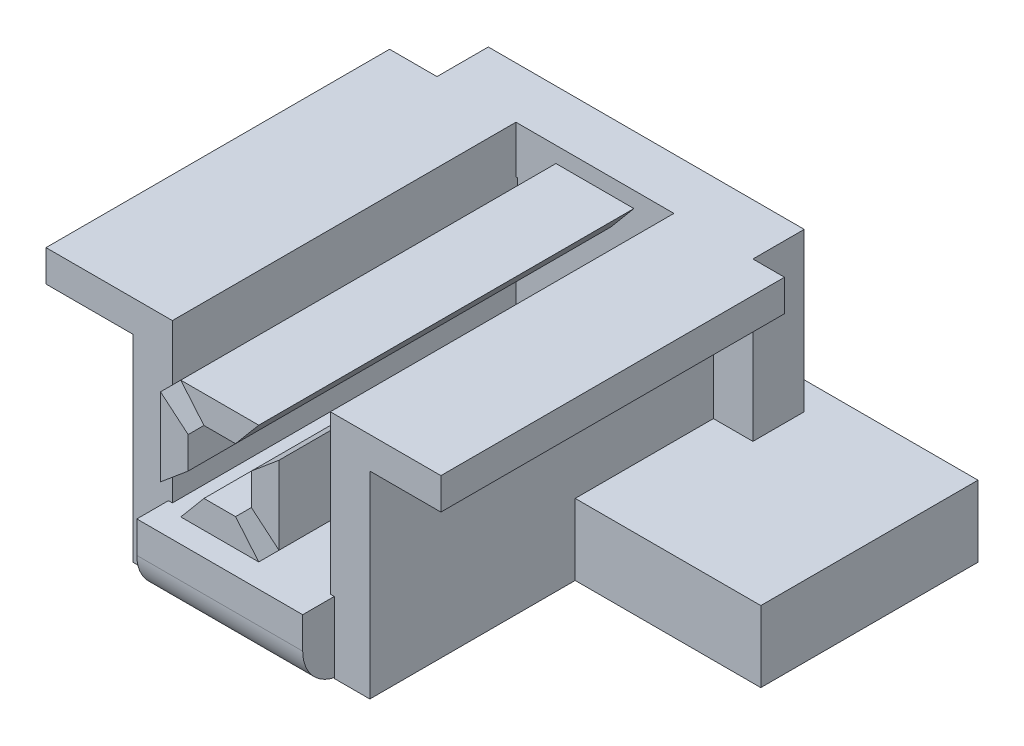
SolidWorks part; units mm, degrees
ref_plane "Front Plane" through (0, 0, 0) normal (0, 0, 1) x (1, 0, 0)
ref_plane "Top Plane" through (0, 0, 0) normal (0, 1, 0) x (1, 0, 0)
ref_plane "Right Plane" through (0, 0, 0) normal (1, 0, 0) x (0, 0, -1)
sketch "Sketch1" plane through (0, 0, 0) normal (0, 1, 0) x (1, 0, 0)
  line L0 (27.5, 55) -> (27.5, 0) construction
  line L1 (5, 0) -> (50, 0)
  line L2 (0, 5) -> (0, 50)
  line L3 (5, 55) -> (50, 55)
  line L4 (55, 5) -> (55, 50)
  line L5 (0, 55) -> (7.5, 55) construction
  line L6 (0, 55) -> (0, 47.5) construction
  line L7 (0, 47.5) -> (7.5, 47.5) construction
  line L8 (7.5, 55) -> (7.5, 47.5) construction
  line L9 (0, 27.5) -> (55, 27.5) construction
  circle A0 centre (7.5, 47.5) radius 2.5
  circle A1 centre (47.5, 47.5) radius 2.5
  circle A2 centre (47.5, 7.5) radius 2.5
  circle A3 centre (7.5, 7.5) radius 2.5
  arc A4 (50, 0) -> (55, 5) centre (50, 5) ccw
  arc A5 (50, 55) -> (55, 50) centre (50, 50) cw
  arc A6 (0, 50) -> (5, 55) centre (5, 50) cw
  arc A7 (5, 0) -> (0, 5) centre (5, 5) cw
  point P23 (55, 55)
  point P29 (0, 0)
  dimension "D3" = 2
  dimension "D5" = 5
  dimension "D1" = 55
  dimension "D2" = 55
  dimension "D4" = 2
extrude "Boss-Extrude2" add sketch "Sketch1" along normal blind 8 and the other way blind 1
sketch "Sketch2" plane through (0, 8, 0) normal (0, 1, 0) x (1, 0, 0)
  line L0 (0, 27.5) -> (55, 27.5)
  line L1 (0, 50) -> (0, 5) construction
  line L2 (55, 5) -> (55, 50) construction
  line L4 (0, 27.5) -> (55, 27.5)
  line L5 (0, 27.5) -> (0, 55)
  line L6 (0, 55) -> (55, 55)
  line L7 (55, 27.5) -> (55, 55)
  circle M3 centre (7.5, 47.5) radius 2.5
  line M5 (55, 5) -> (55, 50)
  arc M6 (55, 50) -> (50, 55) centre (50, 50) ccw
  line M7 (50, 55) -> (5, 55)
  arc M8 (5, 55) -> (0, 50) centre (5, 50) ccw
  line M9 (0, 50) -> (0, 5)
  circle M12 centre (47.5, 47.5) radius 2.5
  dimension "D1" = 27.5
extrude "Cut-Extrude1" cut sketch "Sketch2" against normal through all both and the other way through all contours L0 M9 M5 M6 M7 M8 M12 M3
sketch "Sketch3" plane through (0, 0, -27.5) normal (0, 0, -1) x (-1, 0, 0)
  line L0 (0, -1) -> (0, 8) construction
  line L1 (-55, -1) -> (-37.5, -1) construction
  line L2 (-55, -1) -> (-55, 3.5) construction
  line L3 (-55, 3.5) -> (-37.5, 3.5) construction
  line L4 (-37.5, -1) -> (-37.5, 3.5) construction
  line L5 (0, -1) -> (-55, -1) construction
  circle A0 centre (-37.5, 3.5) radius 3.25
  circle A1 centre (-17.5, 3.5) radius 3.25
  point P10 (0, 3.5)
  dimension "D3" = 6.5
  dimension "D4" = 2
  dimension "D5" = 17.5
  dimension "D1" = 4.5
  dimension "D2" = 17.5
  dimension "D6" = 4.5
sketch3d "3DSketch1"
  point P0 (9.6264, 4.1069, -27.5)
sketch "Sketch5" plane through (0, 8, 0) normal (0, 1, 0) x (1, 0, 0)
  line L0 (27.5, 27.5) -> (27.5, 0)
  line L1 (0, 27.5) -> (55, 27.5) construction
  line L2 (5, 0) -> (50, 0) construction
  line L3 (27.5, 27.5) -> (27.5, 24)
  line L5 (27.5, 24) -> (23, 24)
  line L6 (27.5, 24) -> (27.5, 17.5)
  line L7 (27.5, 17.5) -> (23, 17.5)
  line L8 (23, 24) -> (23, 17.5)
  line L9 (27.5, 24) -> (32, 24)
  line L10 (27.5, 24) -> (27.5, 17.5)
  line L11 (27.5, 17.5) -> (32, 17.5)
  line L12 (32, 24) -> (32, 17.5)
  dimension "D1" = 3.5
  dimension "D2" = 6.5
  dimension "D3" = 4.5
  dimension "D4" = 4.5
  dimension "D5" = 6.5
extrude "Cut-Extrude5" cut sketch "Sketch3" against normal blind 15 draft 0.057 contours A0 | A1
extrude "Boss-Extrude3" add sketch "Sketch5" along normal blind 14.5 contours L5 L8 L7 L0 | L12 L9 L0 L11
sketch "Sketch6" plane through (0, 0, -24) normal (0, 0, -1) x (-1, 0, 0)
  line L0 (-27.5, 8) -> (-27.5, 17)
  line L1 (-32, 8) -> (-23, 8) construction
  circle A0 centre (-27.5, 17) radius 4
  dimension "D2" = 8
  dimension "D1" = 9
extrude "Cut-Extrude4" cut sketch "Sketch6" against normal blind 1.5
sketch "Sketch11" plane through (0, 0, -24) normal (0, 0, -1) x (-1, 0, 0)
  line L0 (-27.5, 22.5) -> (-25.5, 22.5)
  line L1 (-32.4368, 26) -> (-22.5632, 26)
  line L2 (-32, 22.5) -> (-23, 22.5) construction
  line L3 (-25.5, 22.5) -> (-27.5, 22.5)
  line L4 (-25.5, 22.5) -> (-29.5, 22.5)
  line L5 (-25.5, 22.5) -> (-25.5, 26)
  line L6 (-25.5, 26) -> (-29.5, 26)
  line L7 (-29.5, 22.5) -> (-29.5, 26)
  line L8 (-22.5632, 26) -> (-25.5, 22.5)
  line L9 (-29.5, 22.5) -> (-32.4368, 26)
  point P10 (-27.5, 26)
  line M9 (-23, 22.5) -> (-32, 22.5)
  dimension "D1" = 2
  dimension "D2" = 4
  dimension "D3" = 3.5
  dimension "D4" = 40
sketch "Sketch12" plane through (0, 8, 0) normal (0, 1, 0) x (1, 0, 0)
  line L0 (27.5, 17.5) -> (27.5, 0)
  line L1 (32, 17.5) -> (23, 17.5) construction
  line L2 (5, 0) -> (50, 0) construction
  line L3 (17, 0) -> (17, -30)
  line L4 (17, 0) -> (38, 0)
  line L5 (27.5, 0) -> (27.5, -30)
  line L6 (17, -30) -> (38, -30)
  line L7 (38, 0) -> (38, -30)
  point P9 (23.9675, 0)
  line M9 (5, 0) -> (50, 0)
  dimension "D1" = 30
  dimension "D2" = 10.5
extrude "Boss-Extrude7" add sketch "Sketch12" against normal blind 9 contours L7 L5 L6 M9 | L3 L6 L5 M9
sketch "Sketch15" plane through (0, 22.5, 0) normal (0, 1, 0) x (1, 0, 0)
  line L0 (32, 24) -> (32, 17.5) construction
  line L1 (32, 17.5) -> (23, 17.5)
  line L2 (32, 17.5) -> (32, 24)
  line L3 (32, 24) -> (23, 24)
  line L4 (23, 17.5) -> (23, 24)
  line L5 (32, 17.5) -> (23, 17.5) construction
extrude "Boss-Extrude8" add sketch "Sketch15" along normal blind 3.5
extrude "Boss-Extrude9" add sketch "Sketch11" against normal blind 54 contours L9 L7 L1 | L7 L5 L1 M9 | L8 L1 L5
fillet "Fillet4" radius 5 1 edges at (27.5, -1, 30)
sketch "Sketch18" plane through (0, 26, 0) normal (0, 1, 0) x (1, 0, 0)
  line L0 (32.4368, -30) -> (32.4368, 24) construction
  line L1 (22.5632, 24) -> (32.4368, 24)
  line L2 (22.5632, 24) -> (22.5632, 17.5)
  line L3 (22.5632, 17.5) -> (32.4368, 17.5)
  line L4 (32.4368, 24) -> (32.4368, 17.5)
  dimension "D1" = 6.5
extrude "Boss-Extrude11" add sketch "Sketch18" along normal blind 0.5
sketch "Sketch20" plane through (0, 8, 0) normal (0, 1, 0) x (1, 0, 0)
  line L0 (27.5, -1030) -> (27.5, 48970) construction
  line L1 (17, -30) -> (38, -30) construction
  line L2 (32, 17.5) -> (23, 17.5) construction
  line L3 (27.5, 17.5) -> (16.5, 17.5)
  line L4 (27.5, 17.5) -> (27.5, 0)
  line L5 (27.5, 0) -> (16.5, 0)
  line L6 (16.5, 17.5) -> (16.5, 0)
  line L7 (27.5, 17.5) -> (16.5, 0) construction
  line L8 (27.5, 0) -> (16.5, 17.5) construction
  line L10 (27.5, 17.5) -> (38.5, 17.5)
  line L11 (27.5, 17.5) -> (27.5, 0)
  line L12 (27.5, 0) -> (38.5, 0)
  line L13 (38.5, 17.5) -> (38.5, 0)
  line L14 (27.5, 17.5) -> (38.5, 0) construction
  line L15 (27.5, 0) -> (38.5, 17.5) construction
  line L16 (38.5, 17.5) -> (42.5, 17.5)
  line L17 (38.5, 17.5) -> (38.5, 0)
  line L18 (38.5, 0) -> (42.5, 0)
  line L19 (42.5, 17.5) -> (42.5, 0)
  line L21 (16.5, 17.5) -> (12.5, 17.5)
  line L22 (16.5, 17.5) -> (16.5, 0)
  line L23 (16.5, 0) -> (12.5, 0)
  line L24 (12.5, 17.5) -> (12.5, 0)
  line L26 (42.5, 0) -> (38.5, 0)
  line L27 (42.5, 0) -> (42.5, 17.5)
  line L28 (42.5, 17.5) -> (38.5, 17.5)
  line L29 (38.5, 0) -> (38.5, 17.5)
  line L30 (16.5, 0) -> (12.5, 0)
  line L31 (16.5, 0) -> (16.5, 17.5)
  line L32 (16.5, 17.5) -> (12.5, 17.5)
  line L33 (12.5, 0) -> (12.5, 17.5)
  point P5 (27.5, -30)
  point P9 (22, 8.75)
  point P14 (33, 8.75)
  line M12 (5, 0) -> (17, 0)
  line M16 (38, 0) -> (50, 0)
  dimension "D2" = 11
  dimension "D3" = 17.5
  dimension "D4" = 4
extrude "Boss-Extrude12" add sketch "Sketch20" along normal blind 18 contours L21 L24 L6 M12 | L19 L16 L13 M16
sketch "Sketch21" plane through (12.5, 0, 0) normal (-1, 0, 0) x (0, 0, 1)
  line L0 (-17.5, 26) -> (-17.5, 8) construction
  line L1 (0, 26) -> (-17.5, 26)
  line L2 (0, 26) -> (0, 24)
  line L3 (0, 24) -> (-17.5, 24)
  line L4 (-17.5, 26) -> (-17.5, 24)
  dimension "D1" = 2
sketch "Sketch22" plane through (12.5, 0, 0) normal (-1, 0, 0) x (0, 0, 1)
  line L1 (-17.5, 24) -> (0, 24)
  line L2 (-17.5, 24) -> (-17.5, 28)
  line L3 (-17.5, 28) -> (0, 28)
  line L4 (0, 24) -> (0, 28)
  dimension "D1" = 4
extrude "Boss-Extrude13" add sketch "Sketch22" along normal blind 11 and the other way blind 4 contours L3 L4 L1 L2
sketch "Sketch25" plane through (0, 28, 0) normal (0, 1, 0) x (1, 0, 0)
  line L2 (1.5, 17.5) -> (16.5, 17.5) construction
  line L3 (1.5, 0) -> (3.5, 0)
  line L4 (1.5, 0) -> (1.5, 17.5)
  line L5 (1.5, 17.5) -> (3.5, 17.5)
  line L6 (3.5, 0) -> (3.5, 17.5)
  dimension "D1" = 2
extrude "Boss-Extrude14" add sketch "Sketch25" along normal blind 41
sketch "Sketch28" plane through (1.5, 0, 0) normal (-1, 0, 0) x (0, 0, 1)
  line L2 (0, 69) -> (-41, 69)
  line L3 (0, 69) -> (0, 24)
  line L4 (0, 24) -> (-41, 24)
  line L5 (-41, 69) -> (-41, 24)
  dimension "D1" = 45
  dimension "D2" = 41
extrude "Boss-Extrude15" add sketch "Sketch28" against normal blind 2
sketch "Sketch29" plane through (1.5, 0, 0) normal (-1, 0, 0) x (0, 0, 1)
  line L1 (0, 24) -> (-5, 24)
  line L2 (0, 24) -> (0, 33)
  line L3 (0, 33) -> (-5, 33)
  line L4 (-5, 24) -> (-5, 33)
  circle A0 centre (-5, 33) radius 1.75
  circle A1 centre (-36, 33) radius 1.75
  circle A2 centre (-36, 64) radius 1.75
  circle A3 centre (-5, 64) radius 1.75
  dimension "D3" = 3.5
  dimension "D6" = 31
  dimension "D1" = 9
  dimension "D2" = 5
  dimension "D7" = 31
  dimension "D4" = 2
  dimension "D5" = 2
extrude "Cut-Extrude8" cut sketch "Sketch29" against normal blind 9 contours A1 | A3 | A0 | A2
sketch "Sketch30" plane through (42.5, 0, 0) normal (1, 0, 0) x (0, 0, -1)
  line L0 (17.5, 26) -> (17.5, 8) construction
  line L1 (0, 26) -> (17.5, 26)
  line L2 (0, 26) -> (0, 24)
  line L3 (0, 24) -> (17.5, 24)
  line L4 (17.5, 26) -> (17.5, 24)
  line L6 (0, 24) -> (17.5, 24)
  line L7 (0, 24) -> (0, 28)
  line L8 (0, 28) -> (17.5, 28)
  line L9 (17.5, 24) -> (17.5, 28)
  line M4 (17.5, 8) -> (17.5, 26)
  line M5 (17.5, 26) -> (0, 26)
  line M6 (0, 26) -> (0, 8)
  dimension "D1" = 2
  dimension "D2" = 4
extrude "Boss-Extrude16" add sketch "Sketch30" along normal blind 9 and the other way blind 4 contours L3 M6 M4 M5 | L9 L8 L7 M5
sketch "Sketch31" plane through (3.5, 0, 0) normal (1, 0, 0) x (0, 0, -1)
  line L1 (41, 69) -> (20.5, 69)
  line L2 (41, 69) -> (41, 47)
  line L3 (41, 47) -> (20.5, 47)
  line L4 (20.5, 69) -> (20.5, 47)
  circle A0 centre (20.5, 47) radius 10
  dimension "D3" = 20
  dimension "D1" = 22
  dimension "D2" = 20.5
extrude "Cut-Extrude9" cut sketch "Sketch31" against normal blind 9 contours L4 A0 L3 | L3 A0 L4
sketch "Sketch32" plane through (0, 0, -17.5) normal (0, 0, -1) x (-1, 0, 0)
  line L1 (-16.5, 28) -> (-3.5, 28)
  line L2 (-16.5, 28) -> (-16.5, 24)
  line L3 (-16.5, 24) -> (-3.5, 24)
  line L4 (-3.5, 28) -> (-3.5, 24)
extrude "Boss-Extrude17" add sketch "Sketch32" along normal blind 23.5
sketch "Sketch33" plane through (0, 8, 0) normal (0, 1, 0) x (1, 0, 0)
  line L0 (38.5, 17.5) -> (38.5, 0)
  line L1 (38.5, 17.5) -> (38, 17.5)
  line L2 (38.5, 0) -> (38, 0)
  line L3 (38, 17.5) -> (38, 0)
  line L4 (16.5, 17.5) -> (16.5, 0)
  line L5 (16.5, 17.5) -> (17, 17.5)
  line L6 (16.5, 0) -> (17, 0)
  line L7 (17, 17.5) -> (17, 0)
  dimension "D1" = 0.5
  dimension "D2" = 0.5
extrude "Boss-Extrude18" add sketch "Sketch33" along normal blind 20
sketch "Sketch34" plane through (0, 0, 0) normal (0, 0, 1) x (1, 0, 0)
  line L0 (42.5, 24) -> (42.5, 8) construction
  line L1 (51.5, 28) -> (42.5, 28)
  line L2 (51.5, 28) -> (51.5, 24)
  line L3 (51.5, 24) -> (42.5, 24)
  line L4 (42.5, 28) -> (42.5, 24)
  line L5 (42.5, 24) -> (51.5, 24) construction
  line L7 (42.5, 28) -> (38, 28)
  line L8 (42.5, 28) -> (42.5, -1)
  line L9 (42.5, -1) -> (38, -1)
  line L10 (38, 28) -> (38, -1)
  line L11 (17, 28) -> (1.5, 28)
  line L12 (17, 28) -> (17, 24)
  line L13 (17, 24) -> (1.5, 24)
  line L14 (1.5, 28) -> (1.5, 24)
  line L15 (12.5, 24) -> (17, 24)
  line L16 (12.5, 24) -> (12.5, -1)
  line L17 (12.5, -1) -> (17, -1)
  line L18 (17, 24) -> (17, -1)
  line M1 (42.5, 8) -> (42.5, 24)
  line M2 (42.5, 24) -> (51.5, 24)
  line M3 (51.5, 24) -> (51.5, 28)
  line M4 (51.5, 28) -> (38, 28)
  line M5 (38, 28) -> (38, 8)
  line M6 (38, 8) -> (38, -1)
  line M7 (38, -1) -> (50, -1)
extrude "Boss-Extrude19" add sketch "Sketch34" along normal blind 26 contours L18 L13 L16 L17 | L11 L14 L13 L12 | L8 L4 M1 M4 M5 M6 M7 | L4 M4 M2 M3
sketch "Sketch35" plane through (0, 0, -17.5) normal (0, 0, 1) x (1, 0, 0)
  line L1 (32.4368, 26.5) -> (22.5632, 26.5)
  line L2 (32.4368, 26.5) -> (32.4368, 26)
  line L3 (32.4368, 26) -> (22.5632, 26)
  line L4 (22.5632, 26.5) -> (22.5632, 26)
extrude "Boss-Extrude20" add sketch "Sketch35" along normal blind 47.5
sketch "Sketch37" plane through (0, 0, -17.5) normal (0, 0, 1) x (1, 0, 0)
  line L0 (27.5, 8) -> (29.5, 8)
  line L2 (32, 8) -> (23, 8) construction
  line L3 (29.5, 12) -> (33.1362, 7.6666)
  line L4 (29.5, 8) -> (25.5, 8)
  line L5 (29.5, 8) -> (29.5, 12)
  line L6 (29.5, 12) -> (25.5, 12)
  line L7 (25.5, 8) -> (25.5, 12)
  line L8 (25.5, 12) -> (21.8638, 7.6666)
  line L9 (21.8638, 7.6666) -> (33.1362, 7.6666)
  line M8 (32, 8) -> (32, 25.4794)
  line M12 (23, 25.4794) -> (23, 8)
  line M13 (23, 8) -> (32, 8)
  dimension "D1" = 2
  dimension "D2" = 4
  dimension "D3" = 4
  dimension "D4" = 40
  dimension "D5" = 40
extrude "Boss-Extrude21" add sketch "Sketch37" along normal blind 47.5 contours L7 L8 M12 M13 | L7 L5 L6 M13 | L5 L3 M13 M8 | L8 L9 L3 M8 M13 M12
sketch "Sketch38" plane through (0, 0, 30) normal (0, 0, 1) x (1, 0, 0)
  line L1 (22.5632, 26.5) -> (22.1436, 26.5)
  line L2 (22.5632, 26.5) -> (22.5632, 8)
  line L3 (22.5632, 8) -> (22.1436, 8)
  line L4 (22.1436, 26.5) -> (22.1436, 8)
  line L5 (32.4368, 26.5) -> (32.8564, 26.5)
  line L6 (32.4368, 26.5) -> (32.4368, 8)
  line L7 (32.4368, 8) -> (32.8564, 8)
  line L8 (32.8564, 26.5) -> (32.8564, 8)
extrude "Cut-Extrude10" cut sketch "Sketch38" against normal blind 90.5
sketch "Sketch39" plane through (0, 0, 30) normal (0, 0, 1) x (1, 0, 0)
  line L0 (27.784, 26.1035) -> (27.5, 26.5)
  line L1 (32.4368, 26.5) -> (38, 26.5)
  line L2 (32.4368, 26.5) -> (32.4368, 8)
  line L3 (32.4368, 8) -> (38, 8)
  line L4 (38, 26.5) -> (38, 8)
  line L5 (32.4368, 26.5) -> (22.5632, 26.5) construction
  line L6 (27.5, 26.5) -> (27.5, 8)
  line L7 (38, 17.25) -> (38, 19.25)
  line L8 (34, 19.25) -> (38, 22.6064)
  line L9 (38, 19.25) -> (34, 19.25)
  line L10 (38, 19.25) -> (38, 15.25)
  line L11 (38, 15.25) -> (34, 15.25)
  line L12 (34, 19.25) -> (34, 15.25)
  line L13 (34, 15.25) -> (38, 11.8936)
  line L14 (22.5632, 8.5) -> (21.9673, 8)
  line L15 (17, 8) -> (22.5632, 8) construction
  line L16 (17, 22.6064) -> (17.7151, 22.6064)
  line L17 (38, 22.6064) -> (37.2849, 22.6064)
  line L18 (38, 22.6064) -> (38, 22.0064)
  line L19 (38, 22.0064) -> (37.2849, 22.0064)
  line L20 (37.2849, 22.6064) -> (37.2849, 22.0064)
  line L21 (38, 11.8936) -> (37.2849, 11.8936)
  line L22 (38, 11.8936) -> (38, 12.4936)
  line L23 (38, 12.4936) -> (37.2849, 12.4936)
  line L24 (37.2849, 11.8936) -> (37.2849, 12.4936)
  line L25 (17.7151, 22.6064) -> (17.7151, 22.0064)
  line L26 (17, 22.0064) -> (17.7151, 22.0064)
  line L27 (21, 19.25) -> (17, 22.6064)
  line L28 (21, 19.25) -> (21, 15.25)
  line L29 (17, 19.25) -> (21, 19.25)
  line L30 (17.7151, 11.8936) -> (17.7151, 12.4936)
  line L31 (17, 11.8936) -> (17.7151, 11.8936)
  line L32 (17, 12.4936) -> (17.7151, 12.4936)
  line L33 (17, 26.5) -> (17, 8)
  line L34 (17, 15.25) -> (21, 15.25)
  line L35 (21, 15.25) -> (17, 11.8936)
  line L36 (17, 19.25) -> (17, 22.0064)
  line L37 (17, 22.0064) -> (17.7151, 22.0064)
  line L38 (17.7151, 22.0064) -> (21, 19.25)
  line L39 (17, 19.25) -> (21, 19.25)
  dimension "D1" = 2
  dimension "D2" = 4
  dimension "D3" = 4
  dimension "D4" = 40
  dimension "D5" = 40
  dimension "D6" = 0.6
  dimension "D7" = 0.6
extrude "Boss-Extrude23" add sketch "Sketch39" against normal blind 47.5 contours L26 L33 L29 L27 | L33 L34 L28 L29 | L35 L34 L33 L32 | L23 L4 L11 L13 | L9 L12 L11 L4 | L4 L19 L8 L9
ref_plane "Plane1" through (5, 8, 0) normal (0, 1, 0) x (1, 0, 0)
sketch "Sketch45" plane through (0, 8, 0) normal (0, 1, 0) x (1, 0, 0)
  line L0 (0, 15.4413) -> (0, -89.262) construction
  line L1 (-11, 15.4413) -> (-11, -89.262)
  dimension "D1" = 11
sketch "Sketch46" plane through (0, 0, 0) normal (-1, 0, 0) x (0, 0, 1)
  line L1 (-27.5, -1) -> (-5, -1)
  line L2 (-27.5, -1) -> (-27.5, 8)
  line L3 (-27.5, 8) -> (-5, 8)
  line L4 (-5, -1) -> (-5, 8)
  line L5 (-27.5, 8) -> (0, 8)
  line L6 (-27.5, 8) -> (-27.5, -1)
  line L7 (-27.5, -1) -> (0, -1)
  line L8 (0, 8) -> (0, -1)
  line M2 (-27.5, 8) -> (-27.5, -1)
  line M3 (-27.5, -1) -> (-5, -1)
  line M4 (-5, -1) -> (-5, 8)
  line M5 (-5, 8) -> (-27.5, 8)
  dimension "D1" = 27.5
extrude "Boss-Extrude26" add sketch "Sketch46" against normal blind 11.5 contours M5 M2 M3 M4 | L8 L5 L7 M4
sketch "Sketch47" plane through (0, 0, 0) normal (-1, 0, 0) x (0, 0, 1)
  line L1 (-27.5, 8) -> (0, 8)
  line L2 (-27.5, 8) -> (-27.5, -1)
  line L3 (-27.5, -1) -> (0, -1)
  line L4 (0, 8) -> (0, -1)
extrude "Boss-Extrude27" add sketch "Sketch47" along normal blind 11
sketch "Sketch48" plane through (0, 8, 0) normal (0, 1, 0) x (1, 0, 0)
  line L0 (12.5, 17.5) -> (12.5, 24)
  line L1 (23, 24) -> (12.5, 24)
  line L2 (23, 24) -> (23, 17.5)
  line L3 (23, 17.5) -> (12.5, 17.5)
  line L4 (12.5, 24) -> (12.5, 17.5)
  line L5 (12.5, 17.5) -> (7.5, 17.5)
  line L6 (12.5, 24) -> (7.5, 24)
  line L7 (7.5, 17.5) -> (7.5, 24)
  line L8 (42.5, 24) -> (42.5, 17.5)
  line L9 (32, 24) -> (42.5, 24)
  line L10 (32, 24) -> (32, 17.5)
  line L11 (32, 17.5) -> (42.5, 17.5)
  line L12 (42.5, 24) -> (42.5, 17.5)
  line L13 (42.5, 24) -> (47.5, 24)
  line L14 (42.5, 17.5) -> (47.5, 17.5)
  line L15 (47.5, 24) -> (47.5, 17.5)
  line M3 (12.5, 17.5) -> (17, 17.5)
  line M8 (22.5632, 17.5) -> (23, 17.5)
  line M9 (23, 17.5) -> (23, 24)
  line M11 (32, 24) -> (32, 17.5)
  line M12 (32, 17.5) -> (32.4368, 17.5)
  line M17 (38, 17.5) -> (42.5, 17.5)
  dimension "D1" = 5
  dimension "D2" = 5
sketch "Sketch49" plane through (0, 0, -24) normal (0, 0, -1) x (-1, 0, 0)
  line L0 (-17.5, 3.5) -> (-27.5, 17)
  line L1 (-27.5, 17) -> (-17.5, 17)
  line L2 (-17.5, 17) -> (-17.5, 3.5)
  line L3 (-27.5, 17) -> (-37.5, 3.5)
  line L4 (-37.5, 3.5) -> (-37.5, 17)
  line L5 (-37.5, 17) -> (-27.5, 17)
  circle A0 centre (-37.5, 17) radius 4
  circle A1 centre (-17.5, 17) radius 4
  dimension "D1" = 8
  dimension "D2" = 8
extrude "Boss-Extrude31" add sketch "Sketch48" along normal blind 18.5 contours L11 L8 L9 M12 M17 M11 | L15 L13 L8 L14 | L3 L1 L0 M8 M9 M3 | L7 L5 L0 L6
sketch "Sketch50" plane through (0, 0, -24) normal (0, 0, -1) x (-1, 0, 0)
  circle A0 centre (-17.5, 17) radius 4
  circle A1 centre (-37.5, 17) radius 4
  dimension "D1" = 8
  dimension "D2" = 8
extrude "Cut-Extrude11" cut sketch "Sketch50" against normal blind 1.5
sketch "Sketch51" plane through (0, 0, -24) normal (0, 0, -1) x (-1, 0, 0)
  line L1 (-32.4593, 12.5515) -> (-22.8331, 12.5515)
  line L2 (-32.4593, 12.5515) -> (-32.4593, 21.6767)
  line L3 (-32.4593, 21.6767) -> (-22.8331, 21.6767)
  line L4 (-22.8331, 12.5515) -> (-22.8331, 21.6767)
extrude "Boss-Extrude32" add sketch "Sketch51" against normal blind 1.5
sketch "Sketch53" plane through (0, 0, -24) normal (0, 0, -1) x (-1, 0, 0)
  line L0 (-27.5, 17) -> (-27.5, 8)
  line L1 (-47.5, 8) -> (-7.5, 8) construction
  line L2 (-27.5, 8) -> (-27.5, 26.5)
  line L3 (-47.5, 26.5) -> (-16.5, 26.5) construction
  line L4 (-27.5, 17.25) -> (-23.5, 17.25)
  line L5 (-23.5, 17.25) -> (-31.5, 17.25)
  line L7 (-31.5, 13.25) -> (-23.5, 13.25)
  line L8 (-31.5, 13.25) -> (-31.5, 21.25)
  line L9 (-31.5, 21.25) -> (-23.5, 21.25)
  line L10 (-23.5, 13.25) -> (-23.5, 21.25)
  line L11 (-31.5, 13.25) -> (-23.5, 21.25) construction
  line L12 (-31.5, 21.25) -> (-23.5, 13.25) construction
  dimension "D1" = 4
  dimension "D2" = 4
  dimension "D3" = 8
  dimension "D4" = 8
sketch "Sketch54" plane through (0, 0, -17.5) normal (0, 0, 1) x (1, 0, 0)
  line L0 (27.5, 22.5) -> (27.5, 14.5)
  line L1 (29.5, 22.5) -> (25.5, 22.5) construction
  line L3 (23.5, 22.5) -> (31.5, 22.5)
  line L4 (23.5, 22.5) -> (23.5, 14.5)
  line L5 (23.5, 14.5) -> (31.5, 14.5)
  line L6 (31.5, 22.5) -> (31.5, 14.5)
  line L7 (23.5, 22.5) -> (31.5, 14.5) construction
  line L8 (23.5, 14.5) -> (31.5, 22.5) construction
  point P4 (27.5, 18.5)
  line M17 (29.5, 22.5) -> (25.5, 22.5)
  dimension "D1" = 8
  dimension "D2" = 8
  dimension "D3" = 8
extrude "Boss-Extrude35" add sketch "Sketch54" along normal blind 47.5 contours L6 L3 L0 L5 M17 | L4 L5 L0 L3 M17
sketch "Sketch55" plane through (0, 0, 30) normal (0, 0, 1) x (1, 0, 0)
  line L1 (32.4368, 26.5) -> (22.5632, 26.5)
  line L2 (32.4368, 26.5) -> (32.4368, 26)
  line L3 (32.4368, 26) -> (22.5632, 26)
  line L4 (22.5632, 26.5) -> (22.5632, 26)
extrude "Cut-Extrude12" cut sketch "Sketch55" against normal blind 47.5
sketch "Sketch56" plane through (0, 0, 26) normal (0, 0, 1) x (1, 0, 0)
  line L1 (38, 28) -> (37.5, 28)
  line L2 (38, 28) -> (38, 8)
  line L3 (38, 8) -> (37.5, 8)
  line L4 (37.5, 28) -> (37.5, 8)
  line L5 (17, 28) -> (17.5, 28)
  line L6 (17, 28) -> (17, 8)
  line L7 (17, 8) -> (17.5, 8)
  line L8 (17.5, 28) -> (17.5, 8)
  dimension "D1" = 0.5
  dimension "D2" = 0.5
extrude "Boss-Extrude36" add sketch "Sketch56" against normal blind 43.5
sketch "Sketch57" plane through (0, 0, 30) normal (0, 0, 1) x (1, 0, 0)
  line L0 (31.5, 20.5) -> (31.5, 16.5)
  line L1 (35, 18.4644) -> (35, 13.5632)
  line L2 (25.5, 22.5) -> (29.5, 22.5)
  line L3 (29.5, 22.5) -> (32.4368, 26)
  line L4 (29.5, 22.5) -> (29.5, 26)
  line L5 (22.5632, 26) -> (32.4368, 26) construction
  line L6 (31.5, 22.5) -> (31.5, 14.5) construction
  line L7 (35, 13.5632) -> (31.5, 16.5)
  line L8 (31.5, 16.5) -> (35, 16.5)
  line L9 (31.5, 16.5) -> (31.5, 20.4288)
  line L10 (31.5, 20.4288) -> (35, 20.4288)
  line L11 (35, 16.5) -> (35, 20.4288)
  line L12 (35, 18.5356) -> (35, 23.4368)
  line L13 (35, 16.5) -> (31.5, 16.5)
  line L14 (35, 16.5) -> (35, 18.5)
  line L15 (35, 18.5) -> (31.5, 18.5)
  line L16 (31.5, 16.5) -> (31.5, 18.5)
  line L17 (35, 23.4368) -> (31.5, 20.5)
  line L18 (27.5, 22.5) -> (27.5, 14.5) construction
  line L19 (23.5, 14.5) -> (31.5, 14.5) construction
  line L20 (20, 13.5632) -> (23.5, 16.5)
  line L21 (23.5, 16.5) -> (20, 16.5)
  line L22 (20, 18.4644) -> (20, 13.5632)
  line L23 (20, 18.5356) -> (20, 23.4368)
  line L24 (20, 23.4368) -> (23.5, 20.5)
  line L25 (23.5, 20.5) -> (23.5, 16.5)
  line L26 (27.5, 18.5) -> (31.5, 18.5) construction
  line L27 (31.5, 18.5) -> (23.5, 18.5) construction
  line L28 (23.5, 20.5) -> (23.5, 16.5)
  line L29 (32.4368, 26) -> (22.5632, 26)
  line L30 (22.5632, 26) -> (25.5, 22.5)
  line L31 (25.5, 14.5) -> (29.5, 14.5)
  line L32 (22.5632, 11) -> (25.5, 14.5)
  line L33 (32.4368, 11) -> (22.5632, 11)
  line L34 (29.5, 14.5) -> (32.4368, 11)
  line L35 (23.5, 16.5) -> (20, 13.5632)
  line L36 (20, 13.5632) -> (20, 23.4368)
  line L37 (20, 23.4368) -> (23.5, 20.5)
  line L38 (23.5, 18.5) -> (23.5, 20.5)
  line M12 (23.5, 22.5) -> (23.5, 14.5)
  line M13 (23.5, 14.5) -> (31.5, 14.5)
  line M14 (31.5, 14.5) -> (31.5, 22.5)
  dimension "D1" = 2
  dimension "D2" = 3.5
  dimension "D3" = 130
extrude "Boss-Extrude37" add sketch "Sketch57" against normal blind 47.5 contours L12 L17 L0 L10 | L15 L11 L10 L9 | L11 L15 L8 L1 M14 | L8 L7 L1 | L34 L32 L33 M13 | L36 L22 L21 L28 L24 L23 M12 | L21 L22 L20
sketch "Sketch58" plane through (0, 0, 30) normal (0, 0, 1) x (1, 0, 0)
  line L1 (38, 22.0064) -> (37.2849, 22.0064)
  line L2 (38, 22.0064) -> (38, 12.4936)
  line L3 (38, 12.4936) -> (37.2849, 12.4936)
  line L4 (37.2849, 22.0064) -> (37.2849, 12.4936)
  line L5 (17, 22.0064) -> (17.7151, 22.0064)
  line L6 (17, 22.0064) -> (17, 12.4936)
  line L7 (17, 12.4936) -> (17.7151, 12.4936)
  line L8 (17.7151, 22.0064) -> (17.7151, 12.4936)
extrude "Cut-Extrude13" cut sketch "Sketch58" against normal blind 4
sketch "Sketch59" plane through (0, 0, 30) normal (0, 0, 1) x (1, 0, 0)
  line L0 (37.2849, 22.0064) -> (35, 20.0891)
  line L1 (35, 20.0891) -> (35, 14.4109)
  line L2 (35, 14.4109) -> (37.2849, 12.4936)
  line L3 (37.2849, 12.4936) -> (37.2849, 22.0064)
  line L4 (17.7151, 22.0064) -> (20, 20.0891)
  line L5 (20, 20.0891) -> (20, 14.4109)
  line L6 (20, 14.4109) -> (17.7151, 12.4936)
  line L7 (20, 14.4109) -> (17.7151, 12.4936) construction
  line L8 (17.7151, 12.4936) -> (17.7151, 22.0064)
extrude "Cut-Extrude15" cut sketch "Sketch59" against normal blind 47.5
sketch "Sketch60" plane through (0, 0, 26) normal (0, 0, 1) x (1, 0, 0)
  line L0 (17.7151, 12.4936) -> (17.7151, 22.0064) construction
  line L1 (37.2849, 22.0064) -> (37.5, 22.0064)
  line L2 (37.2849, 22.0064) -> (37.2849, 12.4936)
  line L3 (37.2849, 12.4936) -> (37.5, 12.4936)
  line L4 (37.5, 22.0064) -> (37.5, 12.4936)
  line L5 (17.5, 22.0064) -> (17.7151, 22.0064)
  line L6 (17.5, 22.0064) -> (17.5, 12.4936)
  line L7 (17.5, 12.4936) -> (17.7151, 12.4936)
  line L8 (17.7151, 22.0064) -> (17.7151, 12.4936)
extrude "Cut-Extrude16" cut sketch "Sketch60" against normal blind 47.5
sketch "Sketch61" plane through (0, 0, 30) normal (0, 0, 1) x (1, 0, 0)
  line L0 (32.4368, 8) -> (22.5632, 8)
  line L1 (22.5632, 8) -> (22.5632, 8.5)
  line L2 (22.5632, 8.5) -> (24.6609, 11)
  line L3 (24.6609, 11) -> (30.3391, 11)
  line L4 (30.3391, 11) -> (32.4368, 8.5)
  line L5 (32.4368, 8.5) -> (32.4368, 8)
extrude "Cut-Extrude17" cut sketch "Sketch61" against normal blind 47.5
sketch "Sketch62" plane through (0, 0, 30) normal (0, 0, 1) x (1, 0, 0)
  line L1 (23.5, 22.5) -> (31.5, 22.5)
  line L2 (23.5, 22.5) -> (23.5, 14.5)
  line L3 (23.5, 14.5) -> (31.5, 14.5)
  line L4 (31.5, 22.5) -> (31.5, 14.5)
extrude "Cut-Extrude18" cut sketch "Sketch62" against normal blind 47.5
sketch "Sketch63" plane through (0, 0, -41) normal (0, 0, -1) x (-1, 0, 0)
  line L1 (-3.5, 28) -> (-16.5, 28)
  line L2 (-3.5, 28) -> (-3.5, 24)
  line L3 (-3.5, 24) -> (-16.5, 24)
  line L4 (-16.5, 28) -> (-16.5, 24)
extrude "Cut-Extrude20" cut sketch "Sketch63" against normal blind 17
sketch "Sketch64" plane through (0, 0, -17.5) normal (0, 0, -1) x (-1, 0, 0)
  line L1 (-17.5, 26.5) -> (-16.5, 26.5)
  line L2 (-17.5, 26.5) -> (-17.5, 28)
  line L3 (-17.5, 28) -> (-16.5, 28)
  line L4 (-16.5, 26.5) -> (-16.5, 28)
extrude "Boss-Extrude38" add sketch "Sketch64" along normal blind 6.5
sketch "Sketch65" plane through (0, 8, 0) normal (0, 1, 0) x (1, 0, 0)
  line L0 (-11, 0) -> (0, 0)
  line L2 (-11, 27.5) -> (0, 27.5)
  line L3 (-11, 27.5) -> (-11, 0)
  line L4 (0, 0) -> (7.5, 0)
  line L5 (0, 0) -> (0, 7.5)
  line L6 (0, 7.5) -> (7.5, 7.5)
  line L7 (7.5, 0) -> (7.5, 7.5)
  line L8 (-11, 0) -> (0, 0)
  line L9 (0, 27.5) -> (0, 0)
  circle A0 centre (47.5, 7.5) radius 2.5
  circle A1 centre (7.5, 7.5) radius 2.5
  line M13 (55, 27.5) -> (-11, 27.5)
  line M14 (-11, 27.5) -> (-11, 0)
  line M15 (-11, 0) -> (12.5, 0)
  dimension "D1" = 7.5
  dimension "D3" = 5
  dimension "D2" = 7.5
extrude "Cut-Extrude22" cut sketch "Sketch65" against normal blind 9 contours L9 L5 M13 M14 M15 | L7 A1 L6 | L6 A1 L7
fillet "Fillet6" radius 5 1 edges at (0, 3.5, 0)
sketch "Sketch67" plane through (55, 0, 0) normal (1, 0, 0) x (0, 0, -1)
  line L1 (27.5, 8) -> (0, 8)
  line L2 (27.5, 8) -> (27.5, -1)
  line L3 (27.5, -1) -> (0, -1)
  line L4 (0, 8) -> (0, -1)
extrude "Boss-Extrude39" add sketch "Sketch67" along normal blind 11 and the other way blind 10
sketch "Sketch68" plane through (0, 0, -41) normal (0, 0, -1) x (-1, 0, 0)
  line L1 (-1.5, 69) -> (-3.5, 69)
  line L2 (-1.5, 69) -> (-1.5, 24)
  line L3 (-1.5, 24) -> (-3.5, 24)
  line L4 (-3.5, 69) -> (-3.5, 24)
extrude "Cut-Extrude23" cut sketch "Sketch68" against normal blind 17
sketch "Sketch69" plane through (0, 0, -24) normal (0, 0, -1) x (-1, 0, 0)
  line L1 (-3.5, 28) -> (-1.5, 28)
  line L2 (-3.5, 28) -> (-3.5, 69)
  line L3 (-3.5, 69) -> (-1.5, 69)
  line L4 (-1.5, 28) -> (-1.5, 69)
extrude "Cut-Extrude24" cut sketch "Sketch69" against normal blind 37
sketch "Sketch70" plane through (0, 0, -24) normal (0, 0, -1) x (-1, 0, 0)
  line L1 (-17.5, 26.5) -> (-1.5, 26.5)
  line L2 (-17.5, 26.5) -> (-17.5, 28)
  line L3 (-17.5, 28) -> (-1.5, 28)
  line L4 (-1.5, 26.5) -> (-1.5, 28)
  line L5 (-7.5, 24) -> (-1.5, 24)
  line L6 (-7.5, 24) -> (-7.5, 26.5)
  line L7 (-7.5, 26.5) -> (-1.5, 26.5)
  line L8 (-1.5, 24) -> (-1.5, 26.5)
  line M3 (-1.5, 24) -> (-1.5, 28)
  line M10 (-7.5, 24) -> (-1.5, 24)
extrude "Cut-Extrude25" cut sketch "Sketch70" against normal blind 6.5 contours L6 L1 M10 M3
sketch "Sketch71" plane through (0, 26.5, 0) normal (0, 1, 0) x (1, 0, 0)
  line L1 (47.5, 17.5) -> (7.5, 17.5)
  line L2 (47.5, 17.5) -> (47.5, 24)
  line L3 (47.5, 24) -> (7.5, 24)
  line L4 (7.5, 17.5) -> (7.5, 24)
extrude "Boss-Extrude40" add sketch "Sketch71" along normal blind 1.5
